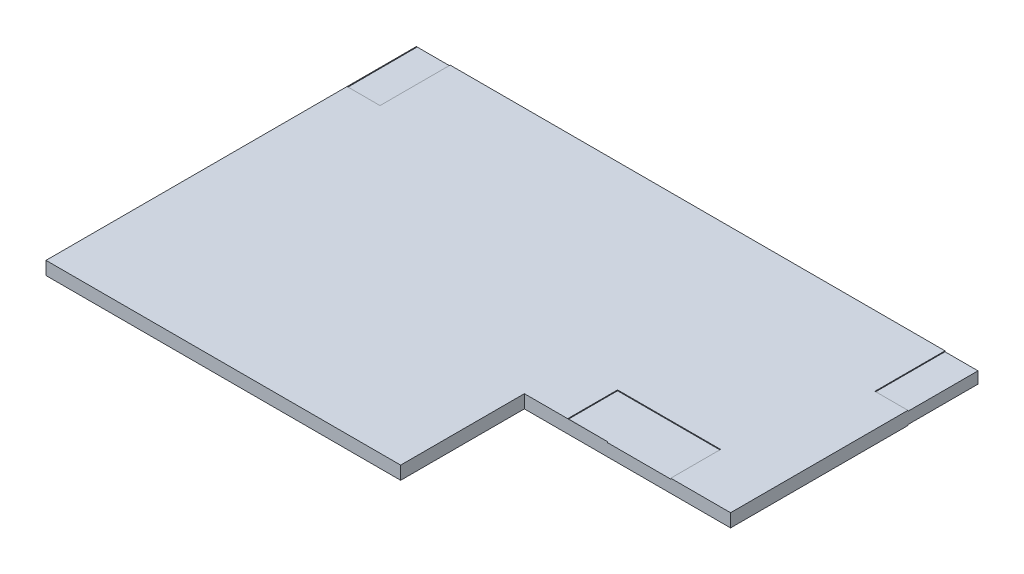
SolidWorks part; units mm, degrees
material "ABS"
ref_plane "Plan de face" through (0, 0, 0) normal (0, 0, 1) x (1, 0, 0)
ref_plane "Plan de dessus" through (0, 0, 0) normal (0, 1, 0) x (1, 0, 0)
ref_plane "Plan de droite" through (0, 0, 0) normal (1, 0, 0) x (0, 0, -1)
sketch "Esquisse1" plane through (0, 0, 0) normal (0, 0, 1) x (1, 0, 0)
  line L0 (23.0111, 70.8023) -> (23.0111, 72.4023)
  line L1 (23.0111, 70.8023) -> (91.0111, 70.8023)
  line L2 (23.0111, 72.4023) -> (91.0111, 72.4023)
  line L3 (91.0111, 70.8023) -> (91.0111, 72.4023)
  line L4 (22.5111, 70.8023) -> (102.0199, 70.8023) construction
  line L5 (22.5111, 72.4023) -> (102.0199, 72.4023) construction
  dimension "D1" = 1.6
extrude "Extrusion1" add sketch "Esquisse1" along normal blind 45
sketch "Esquisse2" plane through (0, 72.4023, 0) normal (0, 1, 0) x (-1, 0, 0)
  line L0 (-91.0111, 64) -> (-66.0111, 64)
  line L2 (-91.0111, 64) -> (-91.0111, 30)
  line L3 (-91.0111, 30) -> (-66.0111, 30)
  line L4 (-66.0111, 64) -> (-66.0111, 30)
extrude "Enlèv. mat.-Extru.1" cut sketch "Esquisse2" against normal blind 2
sketch "Esquisse4" plane through (0, 72.4023, 0) normal (0, 1, 0) x (-1, 0, 0)
  line L0 (-91.0111, 8.5) -> (-87.0111, 8.5)
  line L1 (-92.0112, 7.5) -> (-88.0111, 7.5) construction
  line L2 (-87.0111, 8.5) -> (-87.0111, 0)
  line L3 (-88.0111, -1.6276) -> (-88.0111, 7.5) construction
  line L4 (-27.0111, 8.5) -> (-27.0111, 0)
  line L5 (-27.0111, 8.5) -> (-23.0298, 8.5)
  line L6 (-26.0111, 7.5) -> (-22.0109, 7.5) construction
  line L7 (-26.0111, -1.5843) -> (-26.0111, 7.5) construction
  line L8 (-83.7611, 23.9526) -> (-71.2611, 23.9526)
  line L9 (-71.2611, 29.9478) -> (-71.2611, 23.9526)
  line L10 (-83.7611, 30.0824) -> (-83.7611, 23.9526)
  line L11 (-72.2611, 24.9526) -> (-82.7611, 24.9526) construction
  line L12 (-72.2611, 45.5) -> (-72.2611, 24.9526) construction
  line L13 (-82.7611, 45.5) -> (-82.7611, 24.9526) construction
  line L14 (-91.0111, 8.5) -> (-91.0111, 0)
  line L19 (-91.0111, 0) -> (-87.0111, 0)
  line L20 (-83.7611, 30.0824) -> (-71.2611, 29.9478)
  line L21 (-23.0298, 8.5) -> (-23.0111, 0)
  line L22 (-23.0111, 0) -> (-27.0111, 0)
  dimension "D1" = 1
  dimension "D2" = 1
  dimension "D3" = 1
  dimension "D4" = 1
  dimension "D5" = 1
  dimension "D6" = 1
  dimension "D7" = 1
sketch "Esquisse5" plane through (0, 70.8023, 0) normal (0, -1, 0) x (1, 0, 0)
  line L3 (27.0111, 8.5) -> (27.0111, 0) construction
  line L4 (27.0111, 8.5) -> (23.0298, 8.5) construction
  line L5 (91.0111, 8.5) -> (87.0111, 8.5) construction
  line L6 (87.0111, 8.5) -> (87.0111, 0) construction
  line L7 (23.0298, 8.5) -> (23.0111, 0)
  line L8 (23.0111, 0) -> (27.0111, 0)
  line L9 (87.0111, 0) -> (91.0111, 0)
  line L10 (27.0111, 8.5) -> (27.0111, 0)
  line L11 (27.0111, 8.5) -> (23.0298, 8.5)
  line L12 (91.0111, 8.5) -> (87.0111, 8.5)
  line L13 (87.0111, 8.5) -> (87.0111, 0)
  line L14 (91.0111, 0) -> (91.0111, 8.5)
extrude "Enlèv. mat.-Extru.2" cut sketch "Esquisse4" against normal blind 0.1
extrude "Enlèv. mat.-Extru.3" cut sketch "Esquisse5" against normal blind 0.1
sketch "Esquisse6" plane through (0, 72.4023, 0) normal (0, 1, 0) x (-1, 0, 0)
  line L1 (-64.939, 26.2597) -> (-37.939, 26.2597)
  line L2 (-64.939, 26.2597) -> (-64.939, 12.2597)
  line L3 (-64.939, 12.2597) -> (-37.939, 12.2597)
  line L4 (-37.939, 26.2597) -> (-37.939, 12.2597)
  dimension "D1" = 27
  dimension "D2" = 14
extrude "Enlèv. mat.-Extru.5" [suppressed] cut sketch "Esquisse6" against normal blind 0.1
